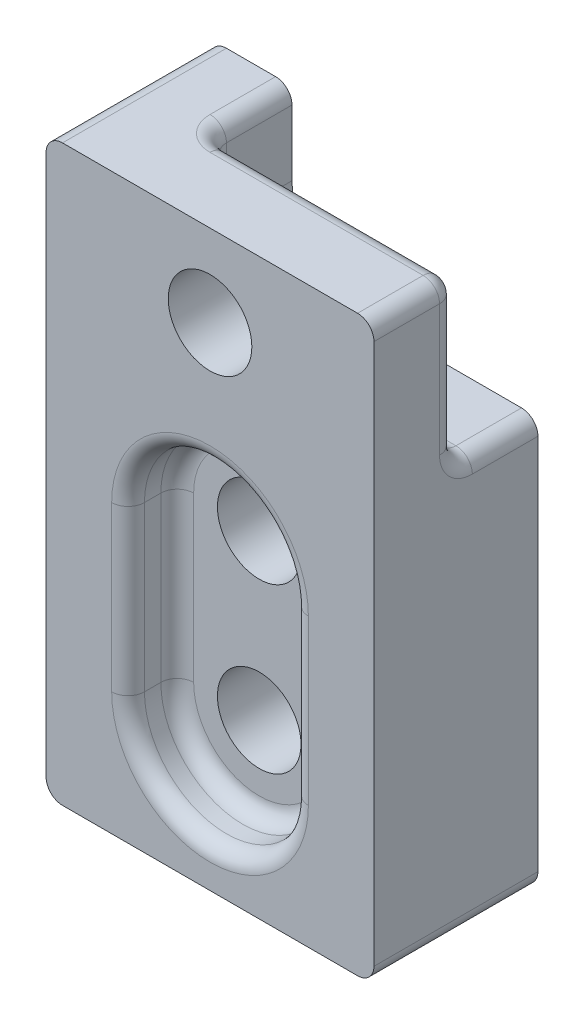
SolidWorks part; units mm, degrees
ref_plane "Front Plane" through (0, 0, 0) normal (0, 0, 1) x (1, 0, 0)
ref_plane "Top Plane" through (0, 0, 0) normal (0, 1, 0) x (1, 0, 0)
ref_plane "Right Plane" through (0, 0, 0) normal (1, 0, 0) x (0, 0, -1)
sketch "Sketch1" plane through (0, 0, 0) normal (0, 0, 1) x (1, 0, 0)
  line L0 (0, 17.5) -> (0, 7.5) construction
  line L1 (-10, -17.5) -> (10, -17.5)
  line L2 (-10, -17.5) -> (-10, 17.5)
  line L4 (10, -17.5) -> (10, 17.5)
  line L5 (0, 7.5) -> (0, 0) construction
  line L6 (-10, 17.5) -> (10, 17.5)
  line L7 (-10, 7.5) -> (10, 7.5) construction
  line L8 (0, -17.5) -> (0, -10) construction
  circle A1 centre (0, -10) radius 2.55
  circle A2 centre (0, 0) radius 2.55
  point P0 (0, 0)
extrude "Boss-Extrude1" add sketch "Sketch1" along normal blind 10
sketch "Sketch2" plane through (0, 0, 0) normal (0, 0, 1) x (1, 0, 0)
  line L0 (0, 17.5) -> (0, 12.5) construction
  line L2 (10, -17.5) -> (10, 17.5) construction
  line L4 (-5, 12.5) -> (-5, 17.5)
  line L5 (0, 7.5) -> (10, 7.5)
  line L8 (10, 17.5) -> (10, 7.5)
  line L9 (-5, 17.5) -> (10, 17.5)
  arc A1 (-5, 12.5) -> (0, 7.5) centre (0, 12.5) ccw
extrude "Cut-Extrude1" cut sketch "Sketch2" along normal blind 5
sketch "Sketch3" plane through (0, 0, 0) normal (0, 0, 1) x (1, 0, 0)
  circle A0 centre (0, 12.5) radius 2.55
extrude "Cut-Extrude2" cut sketch "Sketch3" along normal through all
sketch "Sketch4" plane through (0, 0, 0) normal (0, 0, 1) x (1, 0, 0)
  line L0 (-5, -10) -> (-5, 0)
  line L2 (5, 0) -> (5, -10)
  arc A0 (5, 0) -> (-5, 0) centre (0, 0) ccw
  arc A2 (-5, -10) -> (5, -10) centre (0, -10) ccw
extrude "Cut-Extrude4" cut sketch "Sketch4" against normal blind 3 from surface at 10 starting at face at (2.55, 12.5, 10)
fillet "Fillet1" radius 1 19 edges at (5, -5, 10) (0, -15, 10) (-5, -5, 10) (0, 5, 10) (-10, -17.5, 5) (10, -17.5, 5) (-10, 17.5, 5) (10, 17.5, 7.5) (5, 7.5, 5) (-3.5355, 8.9645, 5) (-5, 15, 5) (5, -5, 7) (0, -15, 7) (-5, -5, 7) (0, 5, 7) (10, 7.5, 2.5) (-5, 17.5, 2.5) (10, 12.5, 5) (2.5, 17.5, 5)
